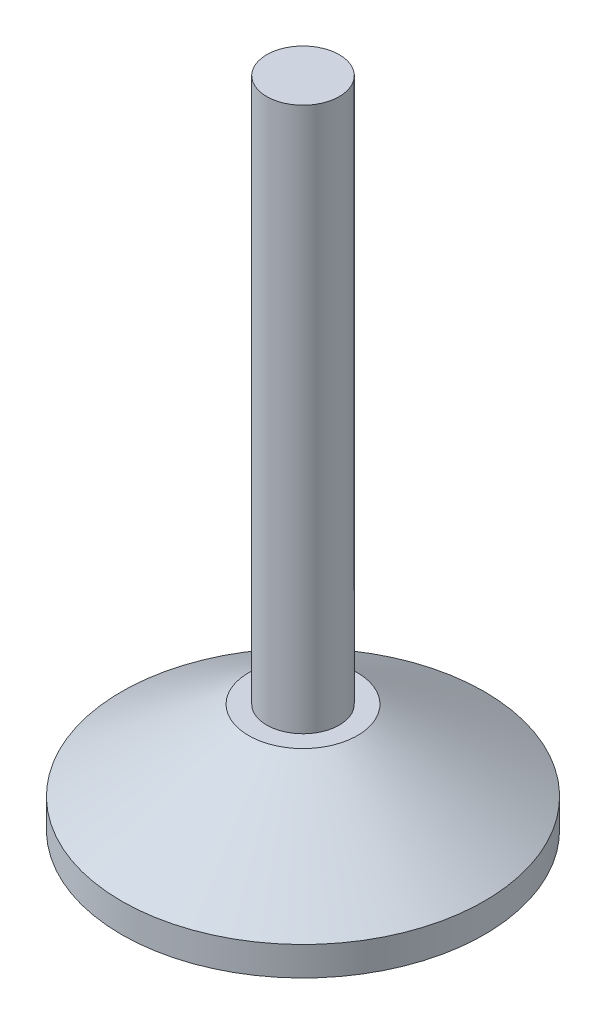
SolidWorks part; units mm, degrees
ref_plane "前视基准面" through (0, 0, 0) normal (0, 0, 1) x (1, 0, 0)
ref_plane "上视基准面" through (0, 0, 0) normal (0, 1, 0) x (1, 0, 0)
ref_plane "右视基准面" through (0, 0, 0) normal (1, 0, 0) x (0, 0, -1)
sketch "草图1" plane through (0, 0, 0) normal (0, 0, 1) x (1, 0, 0)
  line L0 (0, 0) -> (0, 180)
  line L1 (0, 180) -> (10, 180)
  line L2 (10, 180) -> (10, 30)
  line L3 (10, 30) -> (15, 30)
  line L4 (15, 30) -> (50, 8)
  line L5 (50, 8) -> (50, 0)
  line L6 (50, 0) -> (0, 0)
  point P3 (16.3155, 30)
  dimension "D1" = 10
  dimension "D2" = 50
  dimension "D3" = 8
  dimension "D4" = 150
  dimension "D5" = 30
  dimension "D6" = 5
revolve "旋转1" add sketch "草图1" angle 360 about L0
cosmetic thread "装饰螺纹线1" parameters "D1"=145, "D2"=15
